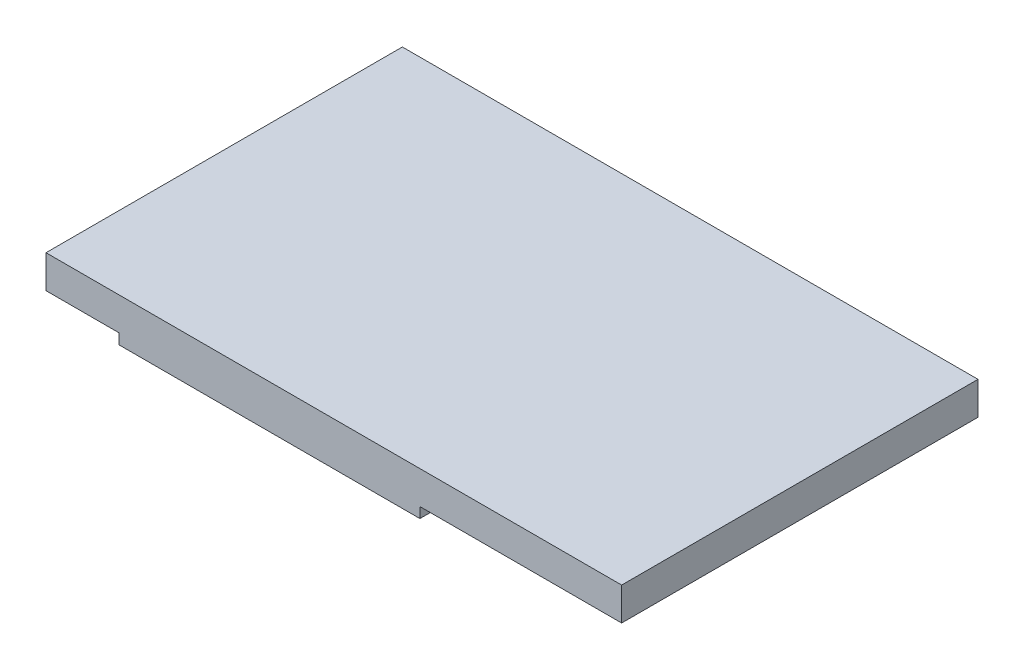
SolidWorks part; units mm, degrees
ref_plane "Front Plane" through (0, 0, 0) normal (0, 0, 1) x (1, 0, 0)
ref_plane "Top Plane" through (0, 0, 0) normal (0, 1, 0) x (1, 0, 0)
ref_plane "Right Plane" through (0, 0, 0) normal (1, 0, 0) x (0, 0, -1)
sketch "Sketch1" plane through (0, 0, 0) normal (0, 1, 0) x (1, 0, 0)
  line L1 (52.5, -32.5) -> (-52.5, -32.5)
  line L2 (52.5, -32.5) -> (52.5, 32.5)
  line L3 (52.5, 32.5) -> (-52.5, 32.5)
  line L4 (-52.5, -32.5) -> (-52.5, 32.5)
  line L5 (52.5, -32.5) -> (-52.5, 32.5) construction
  line L6 (52.5, 32.5) -> (-52.5, -32.5) construction
  point P0 (0, 0)
  dimension "D1" = 105
  dimension "D2" = 65
extrude "Boss-Extrude1" add sketch "Sketch1" along normal blind 6
sketch "Sketch3" plane through (0, 0, 0) normal (0, -1, 0) x (1, 0, 0)
  line L0 (-52.5, 32.5) -> (52.5, 32.5) construction
  line L1 (-39.2, 32.5) -> (15.7, 32.5)
  line L2 (-39.2, 32.5) -> (-39.2, -32.5)
  line L3 (-39.2, -32.5) -> (15.7, -32.5)
  line L4 (15.7, 32.5) -> (15.7, -32.5)
  line L5 (52.5, -32.5) -> (-52.5, -32.5) construction
  line L6 (52.5, 32.5) -> (52.5, -32.5) construction
  line L7 (-52.5, -32.5) -> (-52.5, 32.5) construction
  dimension "D1" = 36.8
  dimension "D2" = 13.3
extrude "Boss-Extrude3" add sketch "Sketch3" along normal blind 1.9
sketch "Sketch4" plane through (0, -1.9, 0) normal (0, -1, 0) x (1, 0, 0)
  line L0 (15.7, 32.5) -> (-39.2, 32.5) construction
  line L1 (-35.9, 27.2) -> (-33.5, 27.2)
  line L2 (-35.9, 27.2) -> (-35.9, 3)
  line L3 (-35.9, 3) -> (-33.5, 3)
  line L4 (-33.5, 27.2) -> (-33.5, 3)
  line L5 (-39.2, 32.5) -> (-39.2, -32.5) construction
  line L6 (-39.2, -32.5) -> (15.7, -32.5) construction
  line L8 (8.2539, 27.2) -> (10.6539, 27.2)
  line L9 (8.2539, 27.2) -> (8.2539, -12.5)
  line L10 (8.2539, -12.5) -> (10.6539, -12.5)
  line L11 (10.6539, 27.2) -> (10.6539, -12.5)
  dimension "D1" = 5.3
  dimension "D2" = 2.4
  dimension "D3" = 3.3
  dimension "D4" = 35.5
  dimension "D5" = 5.3
  dimension "D6" = 2.4
  dimension "D7" = 20
extrude "Boss-Extrude4" add sketch "Sketch4" along normal blind 3.1
